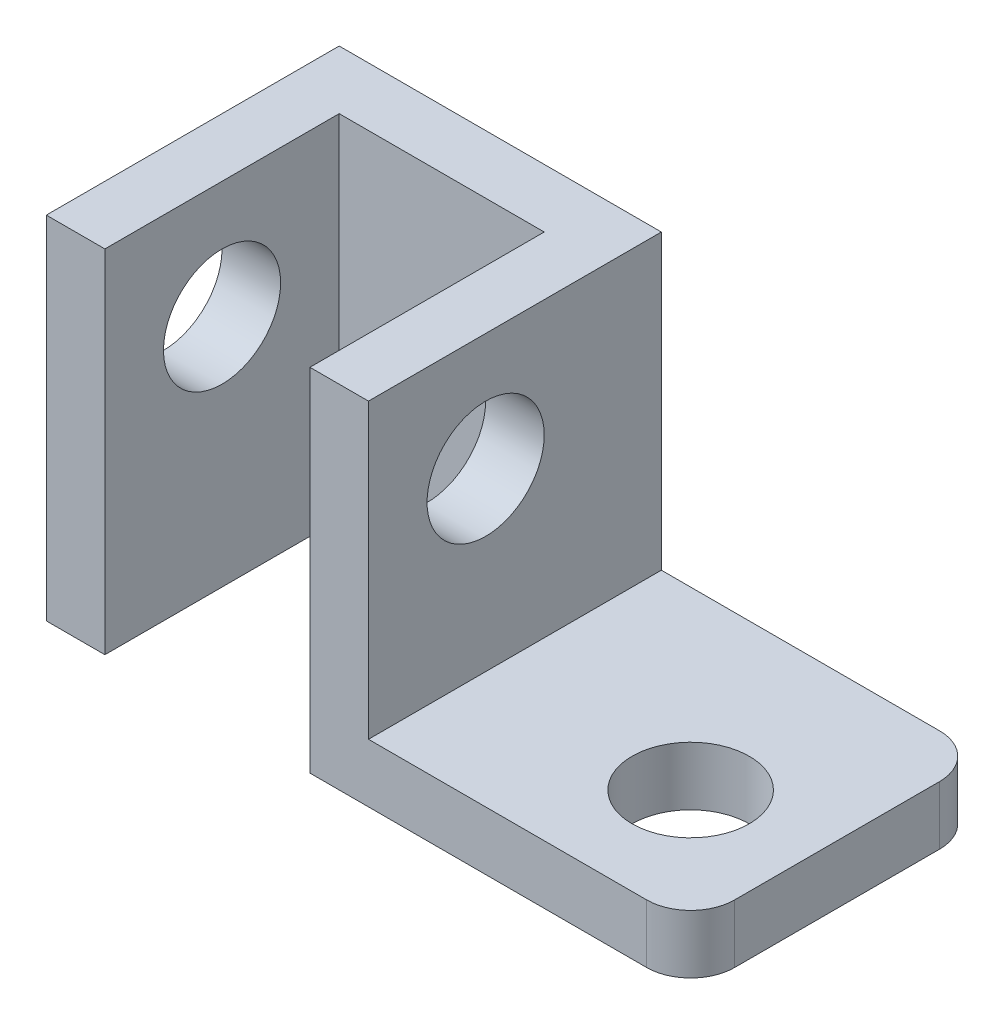
SolidWorks part; units mm, degrees
ref_plane "前视基准面" through (0, 0, 0) normal (0, 0, 1) x (1, 0, 0)
ref_plane "上视基准面" through (0, 0, 0) normal (0, 1, 0) x (1, 0, 0)
ref_plane "右视基准面" through (0, 0, 0) normal (1, 0, 0) x (0, 0, -1)
sketch "草图1" plane through (0, 0, 0) normal (0, 1, 0) x (1, 0, 0)
  line L0 (0, -71.1966) -> (0, 87.6655) construction
  line L1 (-508, -1016) -> (0, -1016)
  line L2 (-2286, 1016) -> (-508, 1016)
  line L3 (-60.3017, 0) -> (40.0322, 0) construction
  line L4 (-2286, 1016) -> (-2286, -1016)
  line L5 (-2794, 1524) -> (0, 1524)
  line L6 (-2794, 1524) -> (-2794, -1016)
  line L7 (-2794, -1016) -> (-2286, -1016)
  line L10 (-508, 1016) -> (-508, -1016)
  line L11 (0, 1524) -> (0, -1016)
sketch "草图3" plane through (0, 0, 0) normal (0, 1, 0) x (1, 0, 0)
  line L0 (0, 1524) -> (0, -1016)
  line L1 (0, 1524) -> (2413, 1524)
  line L2 (0, -1016) -> (2413, -1016)
  line L3 (2794, 1143) -> (2794, -635)
  line L4 (0, -200071.1966) -> (0, 200087.6655) construction
  arc A0 (2413, 1524) -> (2794, 1143) centre (2413, 1143) cw
  arc A1 (2413, -1016) -> (2794, -635) centre (2413, -635) ccw
  dimension "D1" = 0
extrude "凸台-拉伸1" add sketch "草图3" along normal blind 508
sketch "草图4" plane through (0, 0, 0) normal (0, 1, 0) x (1, 0, 0)
  circle A0 centre (1778, 0) radius 508
  point P2 (0, 0)
  point P6 (3282.2413, -352.3218)
  point P12 (2271.0779, -2124.0947)
extrude "切除-拉伸1" cut sketch "草图4" along normal through all both contours A0
extrude "凸台-拉伸2" add sketch "草图1" along normal blind 3048
sketch "草图5" plane through (0, 0, 0) normal (1, 0, 0) x (0, 0, -1)
  line L2 (-1016, 3048) -> (-1016, 508) construction
  circle A0 centre (0, 2032) radius 508
  dimension "D1" = 1016
extrude "切除-拉伸2" cut sketch "草图5" against normal through all both
